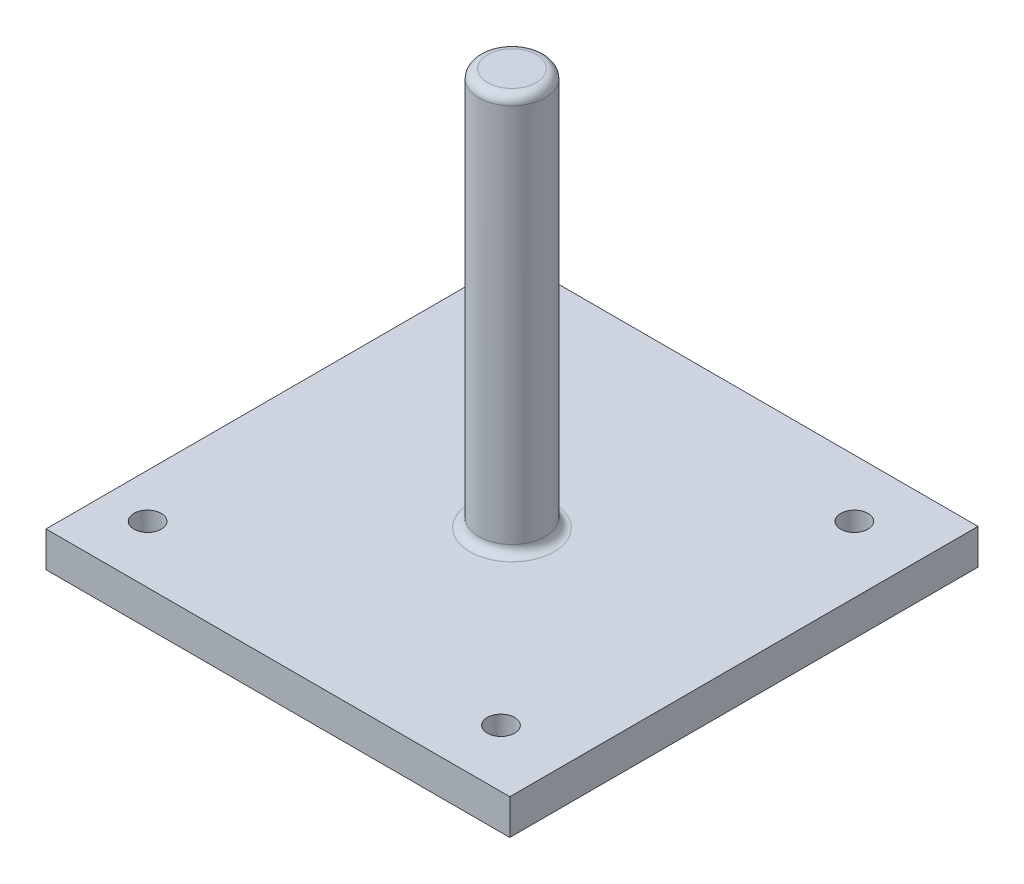
SolidWorks part; units mm, degrees
ref_plane "前视基准面" through (0, 0, 0) normal (0, 0, 1) x (1, 0, 0)
ref_plane "上视基准面" through (0, 0, 0) normal (0, 1, 0) x (1, 0, 0)
ref_plane "右视基准面" through (0, 0, 0) normal (1, 0, 0) x (0, 0, -1)
other "Configuration Table"
sketch "草图1" plane through (0, 0, 0) normal (0, 1, 0) x (1, 0, 0)
  line L1 (0, 0) -> (105, 0)
  line L2 (0, 0) -> (0, 106)
  line L3 (0, 106) -> (105, 106)
  line L4 (105, 0) -> (105, 106)
  line L5 (0, 106) -> (130, 106) construction
  dimension "D1" = 105
extrude "凸台-拉伸1" add sketch "草图1" along normal blind 8
sketch "草图3" plane through (0, 8, 0) normal (0, 1, 0) x (1, 0, 0)
  circle A0 centre (90, 13) radius 3.1
  circle A1 centre (90, 93) radius 3.1
  circle A2 centre (10, 93) radius 3.1
  circle A3 centre (10, 13) radius 3.1
  point P0 (90, 13)
  point P3 (90, 93)
  point P6 (10, 93)
  point P9 (10, 13)
  dimension "D1" = 6.2
extrude "切除-拉伸1" cut sketch "草图3" against normal blind 10
sketch "草图5" plane through (0, 8, 0) normal (0, 1, 0) x (1, 0, 0)
  line L0 (0, 53) -> (105, 53) construction
  line L1 (0, 106) -> (0, 0) construction
  line L2 (105, 0) -> (105, 106) construction
  line L3 (52.5, 106) -> (52.5, 0) construction
  line L4 (105, 106) -> (0, 106) construction
  line L5 (0, 0) -> (105, 0) construction
  circle A0 centre (52.5, 53) radius 7.5
  dimension "D1" = 15
extrude "凸台-拉伸2" add sketch "草图5" along normal blind 90
fillet "圆角1" radius 2 2 edges at (52.5, 8, -60.5) (52.5, 98, -45.5)
